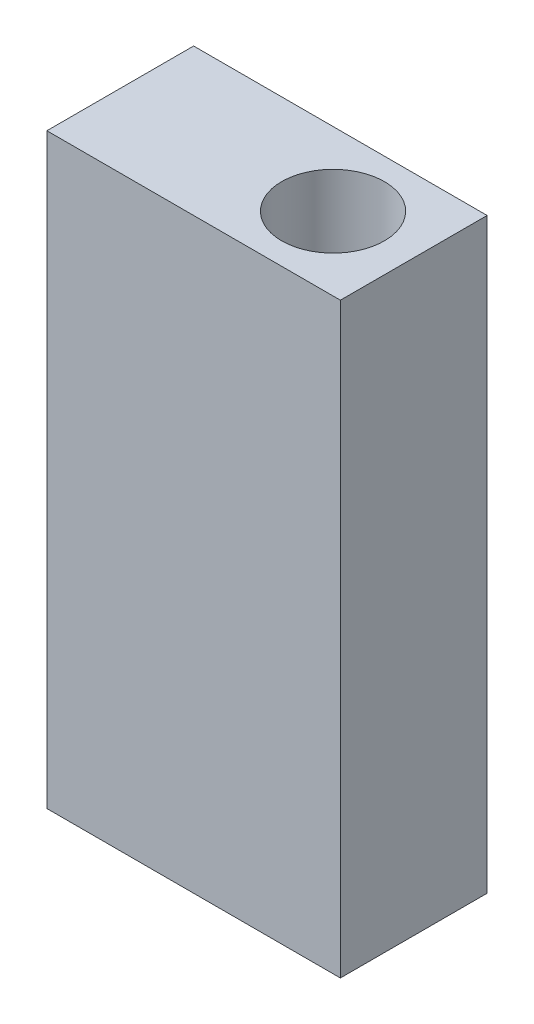
SolidWorks part; units mm, degrees
ref_plane "Front Plane" through (0, 0, 0) normal (0, 0, 1) x (1, 0, 0)
ref_plane "Top Plane" through (0, 0, 0) normal (0, 1, 0) x (1, 0, 0)
ref_plane "Right Plane" through (0, 0, 0) normal (1, 0, 0) x (0, 0, -1)
sketch "Sketch1" plane through (0, 0, 0) normal (0, 1, 0) x (1, 0, 0)
  line L1 (10, 5) -> (-10, 5)
  line L2 (10, 5) -> (10, -5)
  line L3 (10, -5) -> (-10, -5)
  line L4 (-10, 5) -> (-10, -5)
  line L5 (10, 5) -> (-10, -5) construction
  line L6 (10, -5) -> (-10, 5) construction
  circle A0 centre (4.5, 0) radius 3.5
  point P0 (0, 0)
  dimension "D3" = 14.5
  dimension "D1" = 10
  dimension "D2" = 20
  dimension "D4" = 20
extrude "Boss-Extrude1" add sketch "Sketch1" along normal blind 40
sketch "Sketch2" plane through (0, 0, 0) normal (0, 1, 0) x (1, 0, 0)
  circle A0 centre (4.5, 0) radius 3.5
extrude "Boss-Extrude2" add sketch "Sketch2" along normal blind 10
